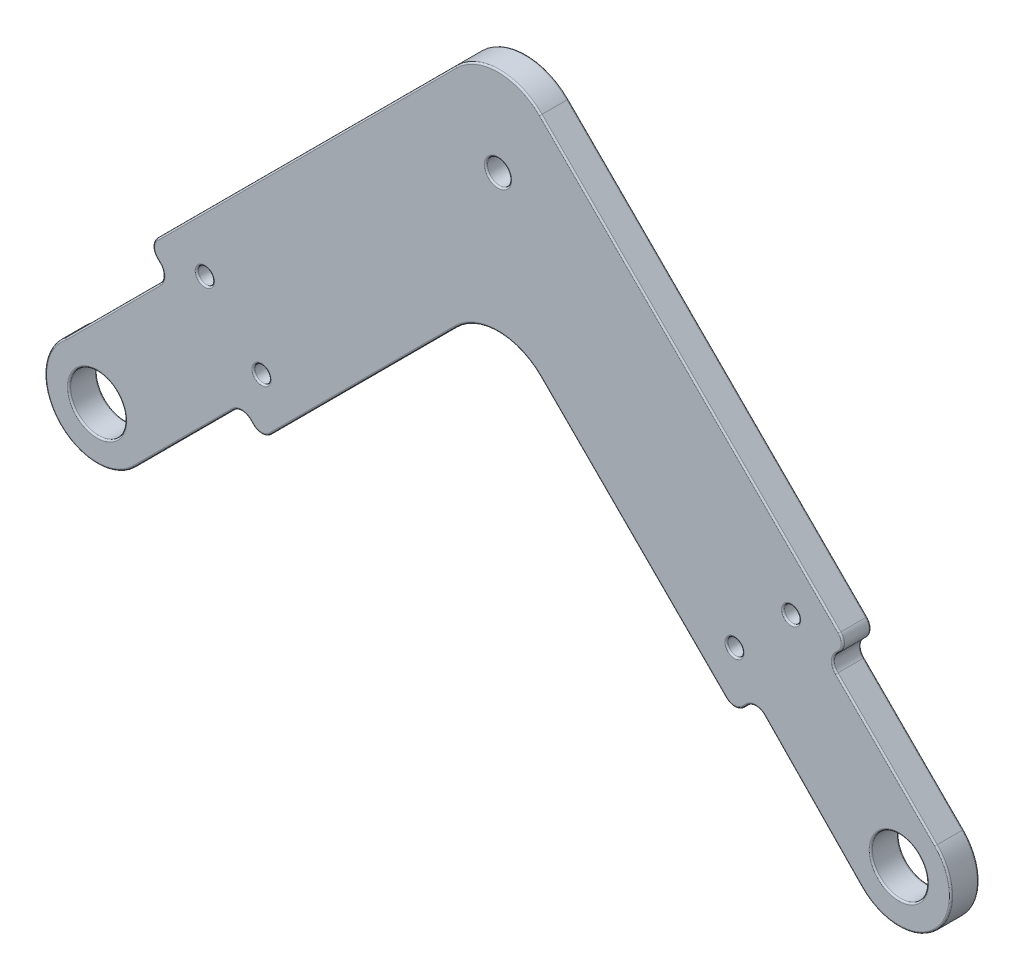
SolidWorks part; units mm, degrees
ref_plane "Front Plane" through (0, 0, 0) normal (0, 0, 1) x (1, 0, 0)
ref_plane "Top Plane" through (0, 0, 0) normal (0, 1, 0) x (1, 0, 0)
ref_plane "Right Plane" through (0, 0, 0) normal (1, 0, 0) x (0, 0, -1)
sketch "Sketch1" plane through (0, 0, 0) normal (0, 0, 1) x (1, 0, 0)
  line L0 (-100, 0) -> (100, 0) construction
  line L1 (-100, 0) -> (0, 100) construction
  line L2 (0, 100) -> (100, 0) construction
  line L3 (0, 0) -> (-50, 50) construction
  line L4 (-40, 60) -> (40, 60) construction
  line L5 (0, 100) -> (0, 60) construction
  circle A0 centre (-100, 0) radius 20
  circle A1 centre (0, 0) radius 20
  circle A2 centre (100, 0) radius 20
  point P3 (0, 0)
  dimension "D5" = 40
  dimension "D1" = 200
  dimension "D2" = 90
  dimension "D3" = 80
  dimension "D4" = 90
sketch "Sketch2" plane through (0, 0, 0) normal (0, 0, 1) x (1, 0, 0)
  line L0 (-56.5165, 43.4835) -> (-40, 60) construction
  line L1 (-100, 0) -> (0, 100) construction
  line L2 (-40, 60) -> (40, 60) construction
  line L3 (40, 60) -> (86.565, 13.435) construction
  line L4 (0, 100) -> (100, 0) construction
  line L5 (-49.4454, 36.4124) -> (-35.8579, 50)
  line L6 (-35.8579, 50) -> (35.8579, 50)
  line L7 (35.8579, 50) -> (79.4939, 6.364)
  line L8 (-63.5876, 50.5546) -> (-44.1421, 70)
  line L9 (-44.1421, 70) -> (44.1421, 70)
  line L10 (44.1421, 70) -> (93.636, 20.5061)
  line L11 (-63.5876, 50.5546) -> (-49.4454, 36.4124)
  line L12 (79.4939, 6.364) -> (93.636, 20.5061)
  line L13 (81.9812, 8.8513) -> (95.0783, -4.2458)
  line L14 (91.1473, 18.0173) -> (104.225, 4.9396)
  line L15 (75.9584, 9.8995) -> (90.1005, 24.0416) construction
  line L16 (0, 100) -> (0, 60) construction
  line L17 (-6, 70) -> (-3.5, 82)
  line L18 (6, 70) -> (3.5, 82)
  circle A0 centre (100, 0) radius 10 construction
  circle A1 centre (100, 0) radius 3.5
  arc A2 (95.0783, -4.2458) -> (104.225, 4.9396) centre (100, 0) ccw
  circle A3 centre (100, 0) radius 0.5
  circle A4 centre (79.4939, 13.435) radius 1
  circle A5 centre (100, 0) radius 6.5 construction
  circle A6 centre (86.565, 20.5061) radius 1
  circle A7 centre (0, 60) radius 1.5
  circle A8 centre (0, 82) radius 1.5
  arc A11 (3.5, 82) -> (-3.5, 82) centre (0, 82) ccw
  circle A12 centre (-50, 50) radius 1.5
  circle A13 centre (0, 82) radius 3.5 construction
  point P30 (106.5, 0)
  point P50 (3.5, 82)
  dimension "D4" = 7
  dimension "D7" = 20
  dimension "D10" = 2
  dimension "D11" = 5
  dimension "D12" = 5
  dimension "D13" = 3
  dimension "D14" = 12
  dimension "D18" = 3
  dimension "D3" = 27.5
  dimension "D8" = 19
  dimension "D9" = 5
  dimension "D16" = 6
  dimension "D17" = 6
  dimension "D1" = 10
  dimension "D2" = 10
  dimension "D5" = 3
  dimension "D6" = 3
  dimension "D15" = 2
sketch "Sketch3" plane through (0, 0, 0) normal (0, 0, 1) x (1, 0, 0)
  line L0 (-86.565, 13.435) -> (-50, 50) construction
  line L1 (-100, 0) -> (0, 100) construction
  line L2 (-50, 50) -> (-13.435, 13.435) construction
  line L3 (0, 0) -> (-50, 50) construction
  line L4 (-79.4939, 6.364) -> (-50, 35.8579)
  line L5 (-50, 35.8579) -> (-20.5061, 6.364)
  line L6 (-93.636, 20.5061) -> (-50, 64.1421)
  line L7 (-50, 64.1421) -> (-6.364, 20.5061)
  line L8 (-94.9578, 19.1843) -> (-50, 64.1421) construction
  line L9 (-80.8157, 5.0422) -> (-50, 35.8579) construction
  line L10 (-93.636, 20.5061) -> (-79.4939, 6.364)
  line L11 (-20.5061, 6.364) -> (-6.364, 20.5061)
  line L12 (-87.8868, 12.1132) -> (-50, 50) construction
  line L13 (-91.121, 17.991) -> (-103.9494, 5.1626)
  line L14 (-81.9688, 8.8389) -> (-95.425, -4.6173)
  line L15 (-17.8509, 9.0191) -> (-4.6576, -4.534)
  line L16 (-8.8388, 18.0312) -> (4.5962, 4.5962)
  line L17 (-90.1005, 24.0416) -> (-75.9584, 9.8995) construction
  line L18 (-24.0416, 9.8995) -> (-9.8995, 24.0416) construction
  circle A0 centre (-100, 0) radius 10 construction
  circle A1 centre (-100, 0) radius 3.5
  circle A2 centre (0, 0) radius 10 construction
  circle A3 centre (0, 0) radius 3.5
  arc A4 (-4.6576, -4.534) -> (4.5962, 4.5962) centre (0, 0) ccw
  circle A5 centre (-100, 0) radius 6.5
  circle A6 centre (0, 0) radius 20 construction
  circle A7 centre (-86.565, 20.5061) radius 1
  circle A8 centre (0, 0) radius 6.5 construction
  circle A9 centre (-79.4939, 13.435) radius 1
  circle A10 centre (-20.5061, 13.435) radius 1
  circle A11 centre (-13.435, 20.5061) radius 1
  point P39 (6.5, 0)
  dimension "D1" = 20
  dimension "D2" = 7
  dimension "D8" = 2
  dimension "D6" = 19
  dimension "D7" = 19
  dimension "D9" = 5
  dimension "D10" = 5
  dimension "D11" = 5
  dimension "D12" = 5
  dimension "D13" = 5
  dimension "D14" = 5
  dimension "D3" = 3
  dimension "D4" = 10
  dimension "D5" = 10
sketch "Sketch4" plane through (0, 0, 0) normal (0, 0, 1) x (1, 0, 0)
  line L1 (57.5, 90.5) -> (57.5, 80.5)
  line L2 (57.5, 80.5) -> (44.1421, 70)
  line L3 (44.1421, 70) -> (-44.1421, 70)
  line L4 (-44.1421, 70) -> (-57.5, 80.5)
  line L5 (-57.5, 80.5) -> (-57.5, 90.5)
  line L6 (-57.5, 90.5) -> (57.5, 90.5)
  line L7 (-4, 60) -> (-4, 70)
  line L8 (4, 60) -> (4, 70)
  line L9 (-22.5, 82) -> (22.5, 82) construction
  line L10 (-22.5, 86.5) -> (22.5, 86.5)
  line L11 (-22.5, 77.5) -> (22.5, 77.5)
  circle A0 centre (0, 60) radius 1.5 construction
  circle A1 centre (0, 60) radius 1.5
  arc A2 (-4, 60) -> (4, 60) centre (0, 60) ccw
  arc A3 (-22.5, 86.5) -> (-22.5, 77.5) centre (-22.5, 82) ccw
  circle A4 centre (0, 60) radius 4 construction
  arc A5 (22.5, 77.5) -> (22.5, 86.5) centre (22.5, 82) ccw
  point P3 (0, 111.8578)
  point P19 (4, 60)
  point P22 (0, 82)
  dimension "D5" = 9
  dimension "D1" = 115
  dimension "D2" = 10
  dimension "D4" = 45
  dimension "D6" = 4
  dimension "D3" = 2.5
sketch "Sketch5" plane through (0, 0, 0) normal (0, 0, 1) x (1, 0, 0)
  line L0 (-81.9688, 8.8389) -> (-95.425, -4.6173) construction
  line L1 (-91.121, 17.991) -> (-103.9494, 5.1626) construction
  line L2 (-17.8509, 9.0191) -> (-4.6576, -4.534) construction
  line L3 (-8.8388, 18.0312) -> (4.5962, 4.5962) construction
  line L4 (-81.9688, 8.8389) -> (-95.425, -4.6173)
  line L5 (-91.121, 17.991) -> (-103.9494, 5.1626)
  line L6 (-79.4939, 6.364) -> (-50, 35.8579)
  line L7 (-50, 35.8579) -> (-20.5061, 6.364)
  line L8 (-20.5061, 6.364) -> (-6.364, 20.5061)
  line L9 (-6.364, 20.5061) -> (-50, 64.1421)
  line L10 (-50, 64.1421) -> (-93.636, 20.5061)
  line L11 (-93.636, 20.5061) -> (-79.4939, 6.364)
  line L12 (-79.4939, 6.364) -> (-50, 35.8579)
  line L13 (-50, 35.8579) -> (-20.5061, 6.364)
  line L14 (-20.5061, 6.364) -> (-17.8509, 9.0191)
  line L15 (-6.364, 20.5061) -> (-50, 64.1421)
  line L16 (-50, 64.1421) -> (-93.636, 20.5061)
  line L17 (-93.636, 20.5061) -> (-91.121, 17.991)
  line L18 (-17.8509, 9.0191) -> (-4.6576, -4.534)
  line L19 (-8.8388, 18.0312) -> (4.5962, 4.5962)
  line L20 (-81.9688, 8.8389) -> (-79.4939, 6.364)
  line L21 (-8.8388, 18.0312) -> (-6.364, 20.5061)
  arc A0 (-4.6576, -4.534) -> (4.5962, 4.5962) centre (0, 0) ccw construction
  circle A1 centre (-100, 0) radius 6.5
  arc A2 (-103.9494, 5.1626) -> (-95.3827, -4.575) centre (-100, 0) ccw
  circle A3 centre (0, 0) radius 3.5
  circle A4 centre (0, 0) radius 3.5
  circle A5 centre (-100, 0) radius 3.5
  circle A6 centre (-100, 0) radius 3.5
  circle A7 centre (-79.4939, 13.435) radius 1
  circle A8 centre (-79.4939, 13.435) radius 1
  circle A9 centre (-86.565, 20.5061) radius 1
  circle A10 centre (-86.565, 20.5061) radius 1
  circle A11 centre (-13.435, 20.5061) radius 1
  circle A12 centre (-13.435, 20.5061) radius 1
  circle A13 centre (-20.5061, 13.435) radius 1
  circle A14 centre (-20.5061, 13.435) radius 1
  arc A15 (-4.6576, -4.534) -> (4.5962, 4.5962) centre (0, 0) ccw
  circle A16 centre (-50, 50) radius 1.5 construction
  circle A17 centre (-50, 50) radius 1.5
  dimension "D1" = 0
  dimension "D2" = 0
  dimension "D3" = 0
  dimension "D4" = 0
  dimension "D5" = 0
  dimension "D6" = 0
  dimension "D7" = 0
  dimension "D8" = 0
extrude "Boss-Extrude1" add sketch "Sketch5" along normal blind 3.5 contours L18 A15 L19 L21 L15 L16 L17 L5 A2 L4 L20 L12 L13 L14 A17 A4 A6 A8 A10 A12 A14
fillet "Fillet1" radius 7.5 2 edges at (-50, 35.8579, 1.75) (-50, 64.1421, 1.75)
fillet "Fillet2" radius 1.5 8 edges at (-20.5061, 6.364, 1.75) (-17.8509, 9.0191, 1.75) (-8.8388, 18.0312, 1.75) (-6.364, 20.5061, 1.75) (-93.636, 20.5061, 1.75) (-91.121, 17.991, 1.75) (-81.9688, 8.8389, 1.75) (-79.4939, 6.364, 1.75)
fillet "Fillet3" radius 0.2 64 edges at (-48.5, 50, 0) (3.5, 0, 0) (-96.5, 0, 0) (-78.4939, 13.435, 0) (-85.565, 20.5061, 0) (-12.435, 20.5061, 0) (-19.5061, 13.435, 0) (-10.724, 1.6979, 0) (4.5652, -4.627, 0) (-1.591, 10.7834, 0) (-7.6014, 19.2687, 0) (-26.0607, 40.2028, 0) (-73.9393, 40.2028, 0) (-92.3785, 19.2486, 0) (-98.0655, 11.0465, 0) (-104.8999, -4.2709, 0) (-89.2272, 1.5805, 0) (-80.7314, 7.6014, 0) (-66.8683, 18.9896, 0) (-33.1317, 18.9896, 0) (-19.1857, 7.6844, 0) (-48.5, 50, 3.5) (3.5, 0, 3.5) (-96.5, 0, 3.5) (-78.4939, 13.435, 3.5) (-85.565, 20.5061, 3.5) (-12.435, 20.5061, 3.5) (-19.5061, 13.435, 3.5) (-10.724, 1.6979, 3.5) (4.5652, -4.627, 3.5) (-1.591, 10.7834, 3.5) (-7.6014, 19.2687, 3.5) (-73.9393, 40.2028, 3.5) (-92.3785, 19.2486, 3.5) (-98.0655, 11.0465, 3.5) (-104.8999, -4.2709, 3.5) (-89.2272, 1.5805, 3.5) (-80.7314, 7.6014, 3.5) (-66.8683, 18.9896, 3.5) (-33.1317, 18.9896, 3.5) (-19.1857, 7.6844, 3.5) (-95.425, -4.6173, 1.75) (-103.9494, 5.1626, 1.75) (-50, 61.0355, 0) (-50, 61.0355, 3.5) (-50, 32.7513, 0) (-50, 32.7513, 3.5) (-79.4939, 6.9853, 0) (-93.0147, 20.5061, 0) (-6.9853, 20.5061, 0) (-20.5061, 6.9853, 0) (-79.4939, 6.9853, 3.5) (-93.0147, 20.5061, 3.5) (-6.9853, 20.5061, 3.5) (-20.5061, 6.9853, 3.5) (-17.8552, 8.3834, 0) (-17.8552, 8.3834, 3.5) (-8.2175, 18.0312, 0) (-8.2175, 18.0312, 3.5) (-91.7423, 17.991, 0) (-91.7423, 17.991, 3.5) (-81.9688, 8.2176, 0) (-81.9688, 8.2176, 3.5) (-26.0607, 40.2028, 3.5)
